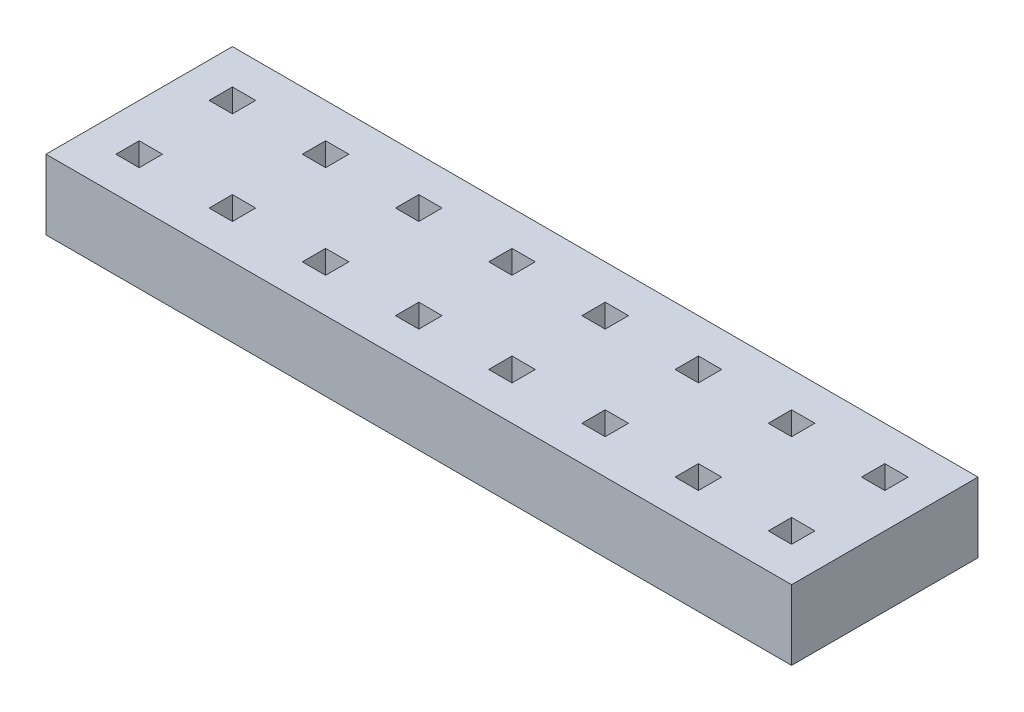
SolidWorks part; units mm, degrees
ref_plane "Front Plane" through (0, 0, 0) normal (0, 0, 1) x (1, 0, 0)
ref_plane "Top Plane" through (0, 0, 0) normal (0, 1, 0) x (1, 0, 0)
ref_plane "Right Plane" through (0, 0, 0) normal (1, 0, 0) x (0, 0, -1)
sketch "Sketch1" plane through (0, 0, 0) normal (0, 1, 0) x (1, 0, 0)
  line L1 (0, 0) -> (16, 0)
  line L2 (0, 0) -> (0, 4)
  line L3 (0, 4) -> (16, 4)
  line L4 (16, 0) -> (16, 4)
extrude "Boss-Extrude1" add sketch "Sketch1" along normal blind 1.5
sketch "Sketch2" plane through (0, 1.5, 0) normal (0, 1, 0) x (1, 0, 0)
  line L0 (2.75, 3.25) -> (3.25, 3.25)
  line L1 (0.75, 3.25) -> (1.25, 3.25)
  line L2 (0.75, 3.25) -> (0.75, 2.75)
  line L3 (0.75, 2.75) -> (1.25, 2.75)
  line L4 (1.25, 3.25) -> (1.25, 2.75)
  line L5 (2.75, 3.25) -> (2.75, 2.75)
  line L6 (2.75, 2.75) -> (3.25, 2.75)
  line L7 (3.25, 3.25) -> (3.25, 2.75)
  line L8 (4.75, 3.25) -> (5.25, 3.25)
  line L9 (4.75, 3.25) -> (4.75, 2.75)
  line L10 (4.75, 2.75) -> (5.25, 2.75)
  line L11 (5.25, 3.25) -> (5.25, 2.75)
  line L12 (6.75, 3.25) -> (7.25, 3.25)
  line L13 (6.75, 3.25) -> (6.75, 2.75)
  line L14 (6.75, 2.75) -> (7.25, 2.75)
  line L15 (7.25, 3.25) -> (7.25, 2.75)
  line L16 (8.75, 3.25) -> (9.25, 3.25)
  line L17 (8.75, 3.25) -> (8.75, 2.75)
  line L18 (8.75, 2.75) -> (9.25, 2.75)
  line L19 (9.25, 3.25) -> (9.25, 2.75)
  line L20 (10.75, 3.25) -> (11.25, 3.25)
  line L21 (10.75, 3.25) -> (10.75, 2.75)
  line L22 (10.75, 2.75) -> (11.25, 2.75)
  line L23 (11.25, 3.25) -> (11.25, 2.75)
  line L24 (12.75, 3.25) -> (13.25, 3.25)
  line L25 (12.75, 3.25) -> (12.75, 2.75)
  line L26 (12.75, 2.75) -> (13.25, 2.75)
  line L27 (13.25, 3.25) -> (13.25, 2.75)
  line L28 (14.75, 3.25) -> (15.25, 3.25)
  line L29 (14.75, 3.25) -> (14.75, 2.75)
  line L30 (14.75, 2.75) -> (15.25, 2.75)
  line L31 (15.25, 3.25) -> (15.25, 2.75)
  line L32 (16.75, 3.25) -> (17.25, 3.25)
  line L33 (16.75, 3.25) -> (16.75, 2.75)
  line L34 (16.75, 2.75) -> (17.25, 2.75)
  line L35 (17.25, 3.25) -> (17.25, 2.75)
  line L36 (18.75, 3.25) -> (19.25, 3.25)
  line L37 (18.75, 3.25) -> (18.75, 2.75)
  line L38 (18.75, 2.75) -> (19.25, 2.75)
  line L39 (19.25, 3.25) -> (19.25, 2.75)
  line L40 (20.75, 3.25) -> (21.25, 3.25)
  line L41 (20.75, 3.25) -> (20.75, 2.75)
  line L42 (20.75, 2.75) -> (21.25, 2.75)
  line L43 (21.25, 3.25) -> (21.25, 2.75)
  line L44 (22.75, 3.25) -> (23.25, 3.25)
  line L45 (22.75, 3.25) -> (22.75, 2.75)
  line L46 (22.75, 2.75) -> (23.25, 2.75)
  line L47 (23.25, 3.25) -> (23.25, 2.75)
  line L48 (24.75, 3.25) -> (25.25, 3.25)
  line L49 (24.75, 3.25) -> (24.75, 2.75)
  line L50 (24.75, 2.75) -> (25.25, 2.75)
  line L51 (25.25, 3.25) -> (25.25, 2.75)
  line L52 (26.75, 3.25) -> (27.25, 3.25)
  line L53 (26.75, 3.25) -> (26.75, 2.75)
  line L54 (26.75, 2.75) -> (27.25, 2.75)
  line L55 (27.25, 3.25) -> (27.25, 2.75)
  line L56 (28.75, 3.25) -> (29.25, 3.25)
  line L57 (28.75, 3.25) -> (28.75, 2.75)
  line L58 (28.75, 2.75) -> (29.25, 2.75)
  line L59 (29.25, 3.25) -> (29.25, 2.75)
  line L60 (30.75, 3.25) -> (31.25, 3.25)
  line L61 (30.75, 3.25) -> (30.75, 2.75)
  line L62 (30.75, 2.75) -> (31.25, 2.75)
  line L63 (31.25, 3.25) -> (31.25, 2.75)
  line L64 (32.75, 3.25) -> (33.25, 3.25)
  line L65 (32.75, 3.25) -> (32.75, 2.75)
  line L66 (32.75, 2.75) -> (33.25, 2.75)
  line L67 (33.25, 3.25) -> (33.25, 2.75)
  line L68 (34.75, 3.25) -> (35.25, 3.25)
  line L69 (34.75, 3.25) -> (34.75, 2.75)
  line L70 (34.75, 2.75) -> (35.25, 2.75)
  line L71 (35.25, 3.25) -> (35.25, 2.75)
  line L72 (0.75, 1.25) -> (1.25, 1.25)
  line L73 (0.75, 1.25) -> (0.75, 0.75)
  line L74 (0.75, 0.75) -> (1.25, 0.75)
  line L75 (1.25, 1.25) -> (1.25, 0.75)
  line L76 (2.75, 1.25) -> (3.25, 1.25)
  line L77 (2.75, 1.25) -> (2.75, 0.75)
  line L78 (2.75, 0.75) -> (3.25, 0.75)
  line L79 (3.25, 1.25) -> (3.25, 0.75)
  line L80 (4.75, 1.25) -> (5.25, 1.25)
  line L81 (4.75, 1.25) -> (4.75, 0.75)
  line L82 (4.75, 0.75) -> (5.25, 0.75)
  line L83 (5.25, 1.25) -> (5.25, 0.75)
  line L84 (6.75, 1.25) -> (7.25, 1.25)
  line L85 (6.75, 1.25) -> (6.75, 0.75)
  line L86 (6.75, 0.75) -> (7.25, 0.75)
  line L87 (7.25, 1.25) -> (7.25, 0.75)
  line L88 (8.75, 1.25) -> (9.25, 1.25)
  line L89 (8.75, 1.25) -> (8.75, 0.75)
  line L90 (8.75, 0.75) -> (9.25, 0.75)
  line L91 (9.25, 1.25) -> (9.25, 0.75)
  line L92 (10.75, 1.25) -> (11.25, 1.25)
  line L93 (10.75, 1.25) -> (10.75, 0.75)
  line L94 (10.75, 0.75) -> (11.25, 0.75)
  line L95 (11.25, 1.25) -> (11.25, 0.75)
  line L96 (12.75, 1.25) -> (13.25, 1.25)
  line L97 (12.75, 1.25) -> (12.75, 0.75)
  line L98 (12.75, 0.75) -> (13.25, 0.75)
  line L99 (13.25, 1.25) -> (13.25, 0.75)
  line L100 (14.75, 1.25) -> (15.25, 1.25)
  line L101 (14.75, 1.25) -> (14.75, 0.75)
  line L102 (14.75, 0.75) -> (15.25, 0.75)
  line L103 (15.25, 1.25) -> (15.25, 0.75)
  line L104 (16.75, 1.25) -> (17.25, 1.25)
  line L105 (16.75, 1.25) -> (16.75, 0.75)
  line L106 (16.75, 0.75) -> (17.25, 0.75)
  line L107 (17.25, 1.25) -> (17.25, 0.75)
  line L108 (18.75, 1.25) -> (19.25, 1.25)
  line L109 (18.75, 1.25) -> (18.75, 0.75)
  line L110 (18.75, 0.75) -> (19.25, 0.75)
  line L111 (19.25, 1.25) -> (19.25, 0.75)
  line L112 (20.75, 1.25) -> (21.25, 1.25)
  line L113 (20.75, 1.25) -> (20.75, 0.75)
  line L114 (20.75, 0.75) -> (21.25, 0.75)
  line L115 (21.25, 1.25) -> (21.25, 0.75)
  line L116 (22.75, 1.25) -> (23.25, 1.25)
  line L117 (22.75, 1.25) -> (22.75, 0.75)
  line L118 (22.75, 0.75) -> (23.25, 0.75)
  line L119 (23.25, 1.25) -> (23.25, 0.75)
  line L120 (24.75, 1.25) -> (25.25, 1.25)
  line L121 (24.75, 1.25) -> (24.75, 0.75)
  line L122 (24.75, 0.75) -> (25.25, 0.75)
  line L123 (25.25, 1.25) -> (25.25, 0.75)
  line L124 (26.75, 1.25) -> (27.25, 1.25)
  line L125 (26.75, 1.25) -> (26.75, 0.75)
  line L126 (26.75, 0.75) -> (27.25, 0.75)
  line L127 (27.25, 1.25) -> (27.25, 0.75)
  line L128 (28.75, 1.25) -> (29.25, 1.25)
  line L129 (28.75, 1.25) -> (28.75, 0.75)
  line L130 (28.75, 0.75) -> (29.25, 0.75)
  line L131 (29.25, 1.25) -> (29.25, 0.75)
  line L132 (30.75, 1.25) -> (31.25, 1.25)
  line L133 (30.75, 1.25) -> (30.75, 0.75)
  line L134 (30.75, 0.75) -> (31.25, 0.75)
  line L135 (31.25, 1.25) -> (31.25, 0.75)
  line L136 (32.75, 1.25) -> (33.25, 1.25)
  line L137 (32.75, 1.25) -> (32.75, 0.75)
  line L138 (32.75, 0.75) -> (33.25, 0.75)
  line L139 (33.25, 1.25) -> (33.25, 0.75)
  line L140 (34.75, 1.25) -> (35.25, 1.25)
  line L141 (34.75, 1.25) -> (34.75, 0.75)
  line L142 (34.75, 0.75) -> (35.25, 0.75)
  line L143 (35.25, 1.25) -> (35.25, 0.75)
  line L144 (1.25, 3.25) -> (1.25, 4) construction
  line L145 (16, 4) -> (0, 4) construction
  line L146 (1.25, 0.75) -> (1.25, 0) construction
  line L147 (0, 0) -> (16, 0) construction
  dimension "D1" = 18
  dimension "D2" = 2
extrude "Cut-Extrude1" cut sketch "Sketch2" against normal blind 2
